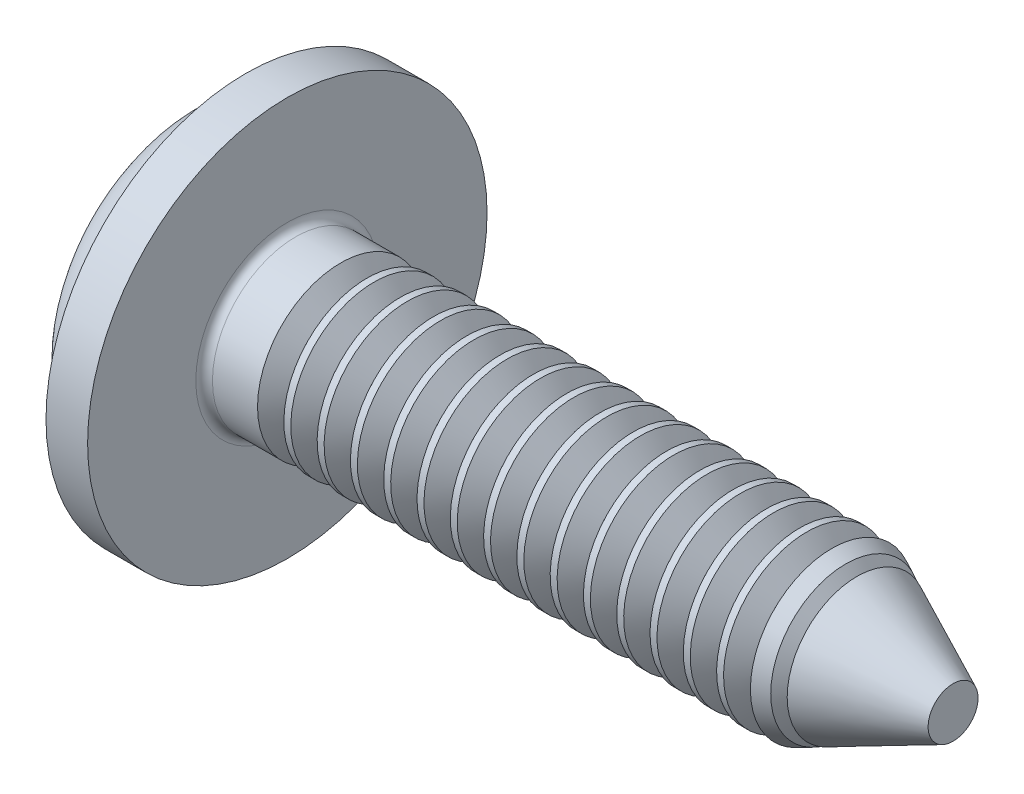
SolidWorks part; units mm, degrees
material "Aço NB 1045"
ref_plane "Plane1" through (0, 0, 0) normal (0, 0, 1) x (1, 0, 0)
ref_plane "Plane2" through (0, 0, 0) normal (0, 1, 0) x (1, 0, 0)
ref_plane "Plane3" through (0, 0, 0) normal (1, 0, 0) x (0, 0, -1)
sketch "BodySke" plane through (0, 0, 0) normal (0, 0, 1) x (1, 0, 0)
  line L0 (1.6, 1) -> (1.6, 2)
  line L1 (1.8, 6.35) -> (1.8, -3.175) construction
  line L2 (-25.4, 0) -> (127, 0) construction
  line L3 (9.6, 0) -> (0, 0)
  line L4 (1.6, 1) -> (9.6, 1)
  line L5 (9.6, 1) -> (9.6, 0)
  line L6 (1.1, 2) -> (1.6, 2)
  line L8 (1.6, 6.35) -> (1.6, -3.175) construction
  arc A0 (0.3941, 1.5765) -> (0, 0) centre (3.35, 0) ccw
  arc A2 (0.3941, 1.5765) -> (1.1, 2) centre (1.1, 1.2) cw
  dimension "D2" = 0.8
  dimension "Length" = 8
  dimension "Head_ht" = 1.6
  dimension "Head_dia" = 4
  dimension "Advance" = 0.4
  dimension "Thread_nom" = 8
  dimension "Diameter" = 2
  dimension "D1" = 0.5
revolve "Base-Revolve" add sketch "BodySke"
cosmetic thread "ThreadCosmetic" [suppressed]
fillet "Fillet1" radius 0.1 1 edges at (1.6, 0, 1)
sketch "Sketch3" plane through (0, 0, 0) normal (1, 0, 0) x (0, 0, -1)
  line L0 (0.24, -1.05) -> (-0.24, -1.05)
  line L1 (0.24, -1.05) -> (0.24, 1.05)
  line L2 (-0.24, 1.05) -> (0.24, 1.05)
  line L3 (-0.24, 1.05) -> (-0.24, -1.05)
  dimension "Cross_dia" = 2.1
  dimension "D1" = 1.05
  dimension "Cross_width" = 0.48
  dimension "D2" = 0.24
ref_plane "Plane4" through (1.42, 0, 0) normal (1, 0, 0) x (0, 0, -1)
sketch "Sketch4" plane through (1.42, 0, 0) normal (1, 0, 0) x (0, 0, -1)
  line L0 (0.24, -0.342) -> (-0.24, -0.342)
  line L1 (0.24, -0.342) -> (0.24, 0.342)
  line L2 (-0.24, 0.342) -> (0.24, 0.342)
  line L3 (-0.24, 0.342) -> (-0.24, -0.342)
  dimension "D1" = 0.48
  dimension "D2" = 0.684
  dimension "D3" = 0.24
  dimension "D4" = 0.342
loft "Recess" cut profiles "Sketch3", "Sketch4"
pattern_circular "RecPat" count 2 every 90 about axis through (0, 0, 0) along (1, 0, 0) of "Recess"
sketch "RecCorSke" plane through (0, 0, 0) normal (0, 0, 1) x (1, 0, 0)
  line L0 (-3.175, 0) -> (15.875, 0) construction
  line L1 (-25.4, 0) -> (127, 0) construction
  line L2 (0, 0) -> (0, 0.4548)
  line L3 (0, 0.4548) -> (1.42, 0.3555)
  line L4 (1.42, 0.3555) -> (1.5355, 0)
  line L5 (1.5355, 0) -> (0, 0)
  dimension "Diameter" = 0.711
  dimension "Depth" = 1.42
  dimension "Draft_angle" = 4
  dimension "Bottom_angle" = 18
revolve "RecessCore" cut sketch "RecCorSke" angle 360 about L0
sketch "ThdSchSke" plane through (0, 0, 0) normal (0, 0, 1) x (1, 0, 0)
  line L0 (2.4, -0.774) -> (2.2418, -1)
  line L1 (2.4, -0.774) -> (2.5582, -1)
  line L2 (2.5582, -1) -> (2.5582, -1.25)
  line L3 (-3.175, 0) -> (5.1513, 0) construction
  line L5 (2.5582, -1.25) -> (2.2418, -1.25)
  line L6 (2.2418, -1.25) -> (2.2418, -1)
  dimension "Diameter" = 2
  dimension "SideAngle" = 55
  dimension "VeeAngle" = 70
  dimension "Thread_minor" = 1.548
  dimension "Overcut" = 2.5
  dimension "Start" = 2.4
revolve "ThreadSchematic" cut sketch "ThdSchSke" angle 360 about L3
pattern_linear "ThdSchPat" count 19 spacing 0.4 along (1, 0, 0) of "ThreadSchematic"
sketch "Esboço1" plane through (1.6, 0, 0) normal (1, 0, 0) x (0, 0, -1)
  circle A0 centre (0, 0) radius 2.4
  dimension "D1" = 4.8
extrude "Ressalto-extrusão1" add sketch "Esboço1" against normal blind 0.5
sketch "Esboço2" plane through (0, 0, 0) normal (0, 1, 0) x (1, 0, 0)
  line L0 (0, 0) -> (9.6, 0) construction
  line L1 (9.6, -0.774) -> (9.6, 0.774) construction
  line L2 (9.6, 0.3) -> (8.1, 1)
  line L4 (8.1, 1) -> (9.6, 1)
  line L5 (9.6, 1) -> (9.6, 0.3)
  line L6 (7.4418, 1) -> (7.3582, 1) construction
  dimension "D1" = 1.5
  dimension "D2" = 0.6
revolve "Corte-Revolução1" cut sketch "Esboço2" angle 360 about L0
scale "Scale1" scale about centroid uniform scaling yes scale factor 0.8
equation "\"D1@Sketch3\" = \"Cross_dia@Sketch3\" / 2"
equation "\"D2@Sketch3\" = \"Cross_width@Sketch3\" / 2"
equation "\"Depth@RecCorSke\" = \"Cross_depth@Plane4\""
equation "\"D1@Sketch4\" = \"Cross_width@Sketch3\""
equation "\"D2@Sketch4\" = \"Cross_dia@Sketch3\" - 2.0 * \"Cross_depth@Plane4\" * tan(26.5  * 0.017453292)"
equation "\"D3@Sketch4\" = \"D1@Sketch4\" / 2"
equation "\"D4@Sketch4\" = \"D2@Sketch4\" / 2"
equation "\"Thread_length@ThreadCosmetic\" = ((sgn( (\"Length@BodySke\" - \"Advance@BodySke\" * 2.0 ) - \"Thread_nom@BodySke\" )-1)*( (\"Length@BodySke\" - \"Advance@BodySke\" * 2.0 ) - \"Thread_nom@BodySke\" ))/-2+ \"Thread_nom@BodySke\""
equation "\"Thread_minor@ThdSchSke\" = \"Thread_minor@ThreadCosmetic\""
equation "\"Diameter@ThdSchSke\" = \"Diameter@BodySke\""
equation "\"Overcut@ThdSchSke\" = \"Diameter@BodySke\" * 1.25"
equation "\"Start@ThdSchSke\" = \"Head_ht@BodySke\" + \"Length@BodySke\" - \"Thread_length@ThreadCosmetic\"  '---Non-countersunk---"
equation "\"Num_threads@ThdSchPat\" = int( \"Thread_length@ThreadCosmetic\" / \"Advance@BodySke\" + 0.999 )  + 1"
equation "\"Advance@ThdSchPat\" = \"Thread_length@ThreadCosmetic\" /  (\"Num_threads@ThdSchPat\" - 1) 'relax it"
